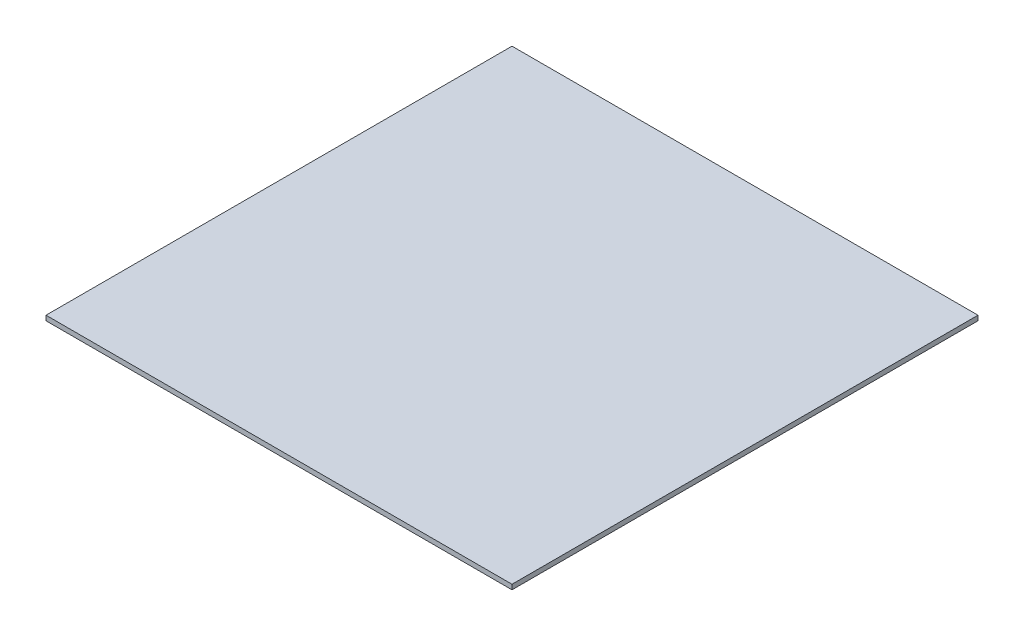
SolidWorks part; units mm, degrees
ref_plane "Front Plane" through (0, 0, 0) normal (0, 0, 1) x (1, 0, 0)
ref_plane "Top Plane" through (0, 0, 0) normal (0, 1, 0) x (1, 0, 0)
ref_plane "Right Plane" through (0, 0, 0) normal (1, 0, 0) x (0, 0, -1)
sketch "Sketch1" plane through (0, 0, 0) normal (0, 1, 0) x (1, 0, 0)
  line L1 (609.6, 609.6) -> (-609.6, 609.6)
  line L2 (609.6, 609.6) -> (609.6, -609.6)
  line L3 (609.6, -609.6) -> (-609.6, -609.6)
  line L4 (-609.6, 609.6) -> (-609.6, -609.6)
  line L5 (609.6, 609.6) -> (-609.6, -609.6) construction
  line L6 (609.6, -609.6) -> (-609.6, 609.6) construction
  point P0 (0, 0)
  dimension "D1" = 1219.2
  dimension "D2" = 1219.2
extrude "Boss-Extrude1" add sketch "Sketch1" along normal blind 12.7 contours L1 L4 L3 L2
